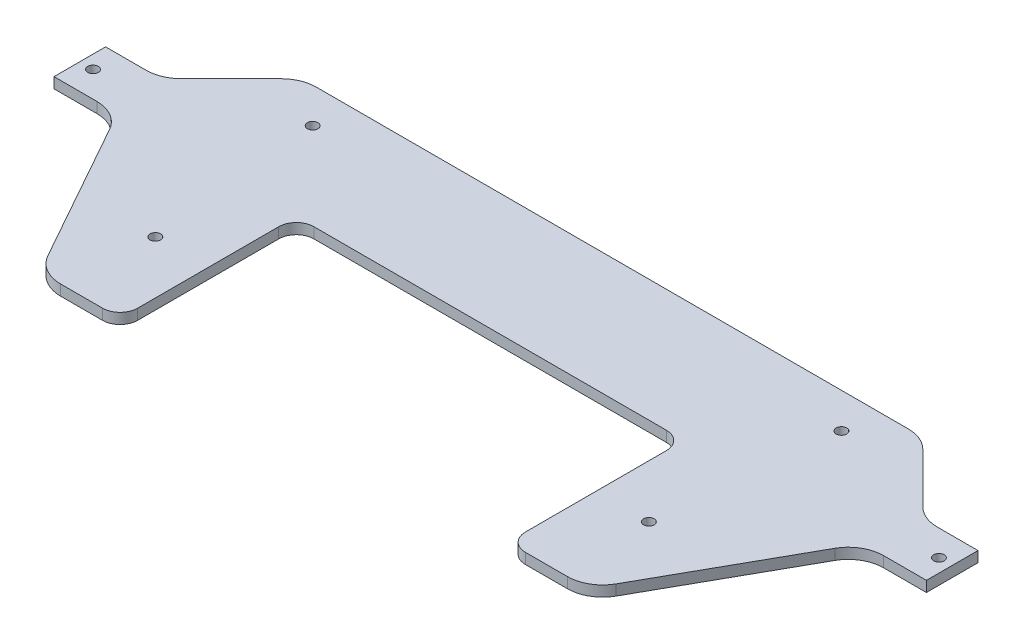
SolidWorks part; units mm, degrees
ref_plane "Alzado" through (0, 0, 0) normal (0, 0, 1) x (1, 0, 0)
ref_plane "Planta" through (0, 0, 0) normal (0, 1, 0) x (1, 0, 0)
ref_plane "Vista lateral" through (0, 0, 0) normal (1, 0, 0) x (0, 0, -1)
sketch "Croquis1" plane through (0, 0, 0) normal (0, 1, 0) x (1, 0, 0)
  line L0 (-27.8825, 0) -> (38.5584, 0) construction
  line L1 (-88.1, 42.3182) -> (88.1, 42.3182)
  line L2 (-77.75, -42.3182) -> (77.75, -42.3182)
  line L3 (-88.1, 42.3182) -> (-108.1, 22.3182)
  line L4 (-108.1, 22.3182) -> (-127.75, 22.3182)
  line L5 (0, 0) -> (0, 27.7067) construction
  line L6 (-127.75, 22.3182) -> (-127.75, 7.6818)
  line L7 (-127.75, 7.6818) -> (-105.75, 7.6818)
  line L8 (-105.75, 7.6818) -> (-77.75, -42.3182)
  line L9 (88.1, 42.3182) -> (108.1, 22.3182)
  line L10 (108.1, 22.3182) -> (127.75, 22.3182)
  line L11 (127.75, 22.3182) -> (127.75, 7.6818)
  line L12 (127.75, 7.6818) -> (105.75, 7.6818)
  line L13 (105.75, 7.6818) -> (77.75, -42.3182)
  dimension "D1" = 255.5
  dimension "D2" = 84.6363
  dimension "D3" = 19.65
  dimension "D4" = 22
  dimension "D5" = 22
  dimension "D6" = 50
  dimension "D7" = 50
  dimension "D8" = 50
  dimension "D9" = 20
  dimension "D10" = 20
extrude "Saliente-Extruir1" add sketch "Croquis1" along normal blind 3
fillet "Redondeo1" radius 10 8 edges at (88.1, 1.5, -42.3182) (-88.1, 1.5, -42.3182) (-77.75, 1.5, 42.3182) (77.75, 1.5, 42.3182) (108.1, 1.5, -22.3182) (105.75, 1.5, -7.6818) (-105.75, 1.5, -7.6818) (-108.1, 1.5, -22.3182)
sketch "Croquis2" plane through (0, 3, 0) normal (0, 1, 0) x (1, 0, 0)
  line L0 (0, 0) -> (0, -87.7887) construction
  line L1 (-119.9961, 22.3182) -> (-119.9961, 40.4374) construction
  line L2 (-112.2421, 22.3182) -> (-127.75, 22.3182) construction
  line L3 (-127.75, 15) -> (-123.2915, 15) construction
  line L4 (-127.75, 22.3182) -> (-127.75, 7.6818) construction
  line L5 (119.9961, 22.3182) -> (119.9961, 29.1715) construction
  line L6 (127.75, 22.3182) -> (112.2421, 22.3182) construction
  line L7 (115.6048, 15) -> (126.3231, 15) construction
  line L8 (83.9579, 42.3182) -> (-83.9579, 42.3182) construction
  line L10 (-71.8888, -42.3182) -> (71.8888, -42.3182) construction
  circle A0 centre (70, -17.3182) radius 1.5
  circle A1 centre (-70, -17.3182) radius 1.5
  circle A2 centre (-119.9961, 15) radius 1.5
  circle A3 centre (119.9961, 15) radius 1.5
  circle A4 centre (-75, 32.3182) radius 1.5
  circle A5 centre (75, 32.3182) radius 1.5
  circle A6 centre (-17.5, -17.3182) radius 1.5
  circle A7 centre (17.5, -17.3182) radius 1.5
  circle A8 centre (-17.5, -37.3182) radius 1.5
  circle A9 centre (17.5, -37.3182) radius 1.5
  dimension "D1" = 3
  dimension "D2" = 3
  dimension "D7" = 3
  dimension "D8" = 3
  dimension "D10" = 3
  dimension "D11" = 3
  dimension "D17" = 3
  dimension "D18" = 3
  dimension "D19" = 3
  dimension "D20" = 3
  dimension "D3" = 75
  dimension "D4" = 75
  dimension "D5" = 10
  dimension "D6" = 10
  dimension "D9" = 140
  dimension "D12" = 25
  dimension "D13" = 35
  dimension "D14" = 35
  dimension "D15" = 5
  dimension "D16" = 20
extrude "Cortar-Extruir1" cut sketch "Croquis2" against normal through all
sketch "Croquis4" plane through (0, 3, 0) normal (0, 1, 0) x (1, 0, 0)
  line L0 (-55, -42.3182) -> (-55, 7.6818)
  line L1 (-55, 7.6818) -> (55, 7.6818)
  line L2 (55, 7.6818) -> (55, -42.3182)
  line L3 (55, -42.3182) -> (-55, -42.3182)
  line L4 (0, 0) -> (0, 21.6247) construction
  line L5 (-71.8888, -42.3182) -> (71.8888, -42.3182) construction
  dimension "D1" = 110
  dimension "D2" = 50
extrude "Cortar-Extruir2" cut sketch "Croquis4" against normal through all
fillet "Redondeo2" radius 5 4 edges at (-55, 1.5, 42.3182) (55, 1.5, 42.3182) (55, 1.5, -7.6818) (-55, 1.5, -7.6818)
sketch "Croquis5" plane through (0, 3, 0) normal (0, 1, 0) x (1, 0, 0)
  line L0 (-127.75, 22.3182) -> (-127.75, 7.6818)
  line L1 (-127.75, 7.6818) -> (-123.75, 7.6818)
  line L2 (-127.75, 7.6818) -> (-111.6112, 7.6818) construction
  line L3 (-123.75, 7.6818) -> (-123.75, 22.3182)
  line L4 (-112.2421, 22.3182) -> (-127.75, 22.3182) construction
  line L5 (-123.75, 22.3182) -> (-127.75, 22.3182)
  line L6 (127.75, 22.3182) -> (127.75, 7.6818)
  line L7 (127.75, 7.6818) -> (123.75, 7.6818)
  line L8 (111.6112, 7.6818) -> (127.75, 7.6818) construction
  line L9 (123.75, 7.6818) -> (123.75, 22.3182)
  line L10 (127.75, 22.3182) -> (112.2421, 22.3182) construction
  line L11 (123.75, 22.3182) -> (127.75, 22.3182)
  dimension "D1" = 4
  dimension "D2" = 4
extrude "Cortar-Extruir3" cut sketch "Croquis5" against normal through all
